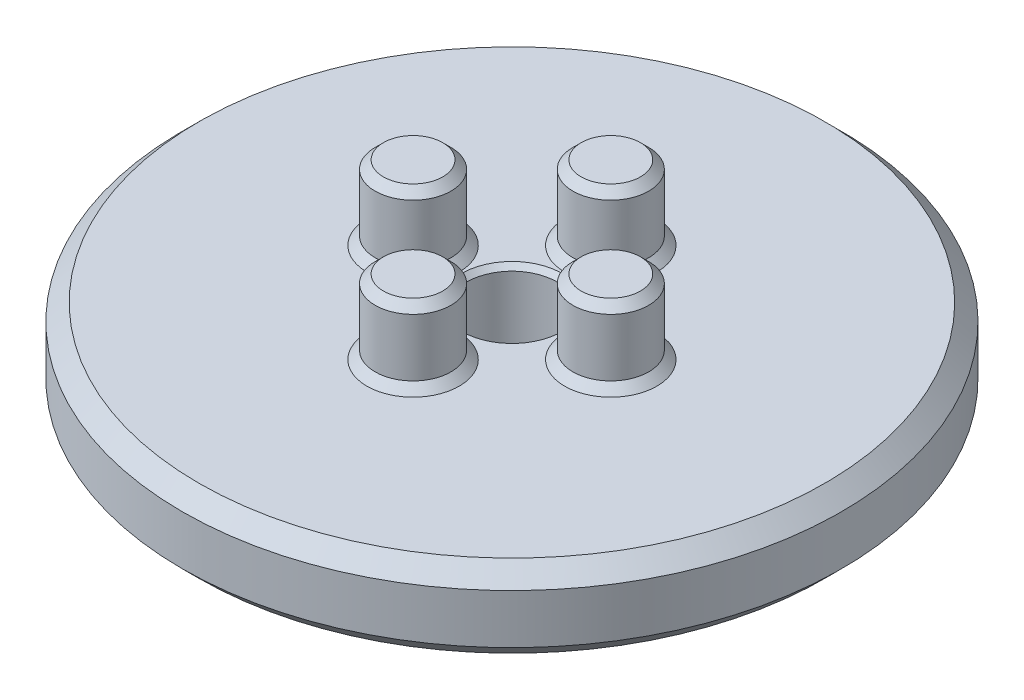
SolidWorks part; units mm, degrees
ref_plane "前视基准面" through (0, 0, 0) normal (0, 0, 1) x (1, 0, 0)
ref_plane "上视基准面" through (0, 0, 0) normal (0, 1, 0) x (1, 0, 0)
ref_plane "右视基准面" through (0, 0, 0) normal (1, 0, 0) x (0, 0, -1)
sketch "草图1" plane through (0, 0, 0) normal (0, 1, 0) x (1, 0, 0)
  circle A0 centre (0, 0) radius 20
  dimension "D1" = 40
extrude "凸台-拉伸1" add sketch "草图1" along normal blind 5
sketch "草图4" plane through (0, 5, 0) normal (0, 1, 0) x (1, 0, 0)
  circle A0 centre (0, 0) radius 2.75
  point P2 (0, 0)
  dimension "D1" = 5.5
extrude "切除-拉伸3" cut sketch "草图4" along normal blind 15 from surface at -5 starting at face at (0, 0, 20)
sketch "草图7" plane through (0, 5, 0) normal (0, 1, 0) x (1, 0, 0)
  circle A0 centre (6, 0) radius 2.3
  point P2 (0, 0)
  dimension "D2" = 4.6
  dimension "D1" = 6
extrude "凸台-拉伸3" add sketch "草图7" along normal blind 4.5
chamfer "倒角3" distance 0.5 angle 45 2 edges at (6, 5, 2.3) (6, 9.5, 2.3)
pattern_circular "阵列(圆周)1" count 4 over 360 about axis through (0, 0, 0) along (0, 1, 0) of "凸台-拉伸3", "倒角3"
chamfer "倒角4" distance 0.3 angle 45 2 edges at (0, 0, 2.75) (0, 5, 2.75)
chamfer "倒角5" distance 1 angle 45 2 edges at (0, 0, 20) (0, 5, 20)
